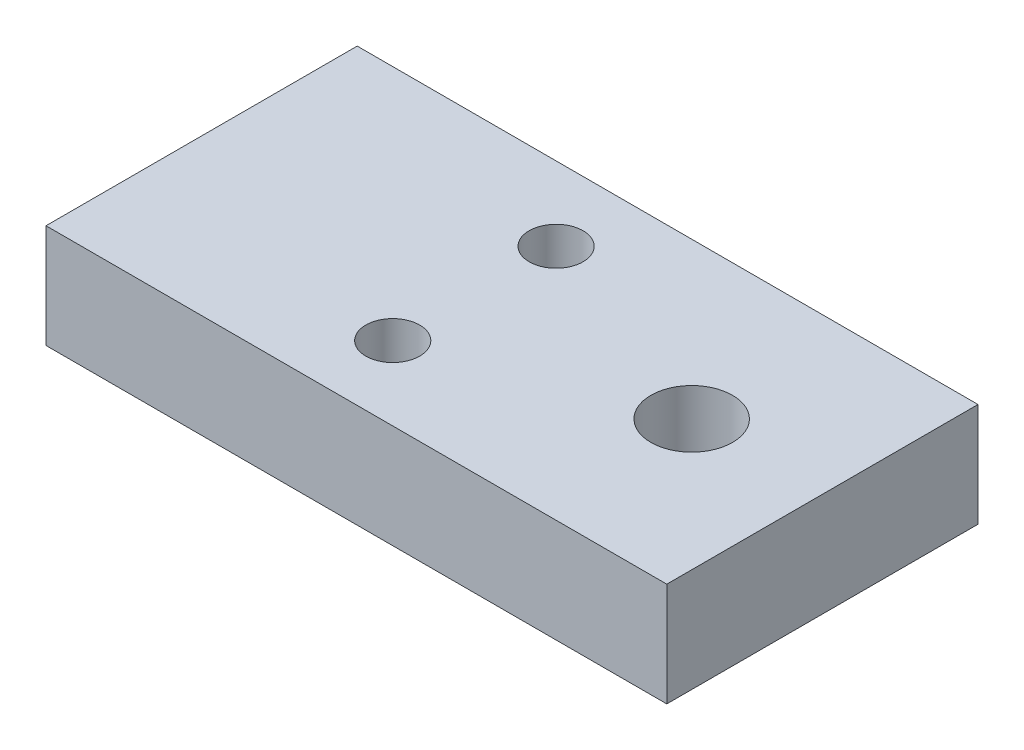
SolidWorks part; units mm, degrees
ref_plane "Front Plane" through (0, 0, 0) normal (0, 0, 1) x (1, 0, 0)
ref_plane "Top Plane" through (0, 0, 0) normal (0, 1, 0) x (1, 0, 0)
ref_plane "Right Plane" through (0, 0, 0) normal (1, 0, 0) x (0, 0, -1)
sketch "Sketch1" plane through (0, 0, 0) normal (0, 1, 0) x (1, 0, 0)
  line L1 (19, -9.525) -> (-19, -9.525)
  line L2 (19, -9.525) -> (19, 9.525)
  line L3 (19, 9.525) -> (-19, 9.525)
  line L4 (-19, -9.525) -> (-19, 9.525)
  line L5 (19, -9.525) -> (-19, 9.525) construction
  line L6 (19, 9.525) -> (-19, -9.525) construction
  point P0 (0, 0)
  dimension "D1" = 19.05
  dimension "D2" = 38
extrude "Boss-Extrude1" add sketch "Sketch1" along normal blind 6.35
sketch "Sketch2" plane through (0, 6.35, 0) normal (0, 1, 0) x (1, 0, 0)
  line L0 (-19, 0) -> (-2.3, 0) construction
  line L1 (-19, 9.525) -> (-19, -9.525) construction
  line L2 (19, 0) -> (11, 0) construction
  line L3 (19, -9.525) -> (19, 9.525) construction
  line L4 (-2.3, 5) -> (-2.3, -5) construction
  circle A0 centre (-2.3, 0) radius 0.7486
  point P10 (11, 0)
  point P12 (-2.3, 0)
  dimension "D1" = 16.7
  dimension "D2" = 8
  dimension "D3" = 10
hole_wizard "M4x0.7 Tapped Hole1" positions "3DSketch1" profile "Sketch3" tap size "M4x0.7" standard "ANSI Metric" end condition through all
sketch3d "3DSketch1"
  point P8 (-2.3, 6.35, -5)
  point P11 (-2.3, 6.35, 5)
sketch "Sketch3" plane through (-2.3, 6.35, -5) normal (1, 0, 0) x (0, 0, 1)
  line L0 (0, 0) -> (0, 6.35)
  line L1 (0, 6.35) -> (1.65, 6.35)
  line L2 (1.65, 6.35) -> (1.65, 0)
  line L5 (1.65, 0) -> (0, 0)
  line L11 (0, -6.35) -> (0, 107.95) construction
  dimension "Thru Tap Drill Dia." = 3.3
  dimension "Thru Tap Drill Depth" = 6.35
cosmetic thread "Hole Thread1" parameters "D2"=4.4
cosmetic thread "Hole Thread3" parameters "D2"=4
hole_wizard "M6x1.0 Tapped Hole1" positions "3DSketch2" profile "Sketch4" tap size "M6x1.0" standard "ANSI Metric" end condition through all
sketch3d "3DSketch2"
  point P0 (11, 6.35, 0)
  point P3 (11, 6.35, 0)
sketch "Sketch4" plane through (11, 6.35, 0) normal (1, 0, 0) x (0, 0, 1)
  line L0 (0, 0) -> (0, 6.35)
  line L1 (0, 6.35) -> (2.5, 6.35)
  line L2 (2.5, 6.35) -> (2.5, 0)
  line L5 (2.5, 0) -> (0, 0)
  line L11 (0, -6.35) -> (0, 107.95) construction
  dimension "Thru Tap Drill Dia." = 5
  dimension "Thru Tap Drill Depth" = 6.35
cosmetic thread "Hole Thread4" parameters "D2"=6
